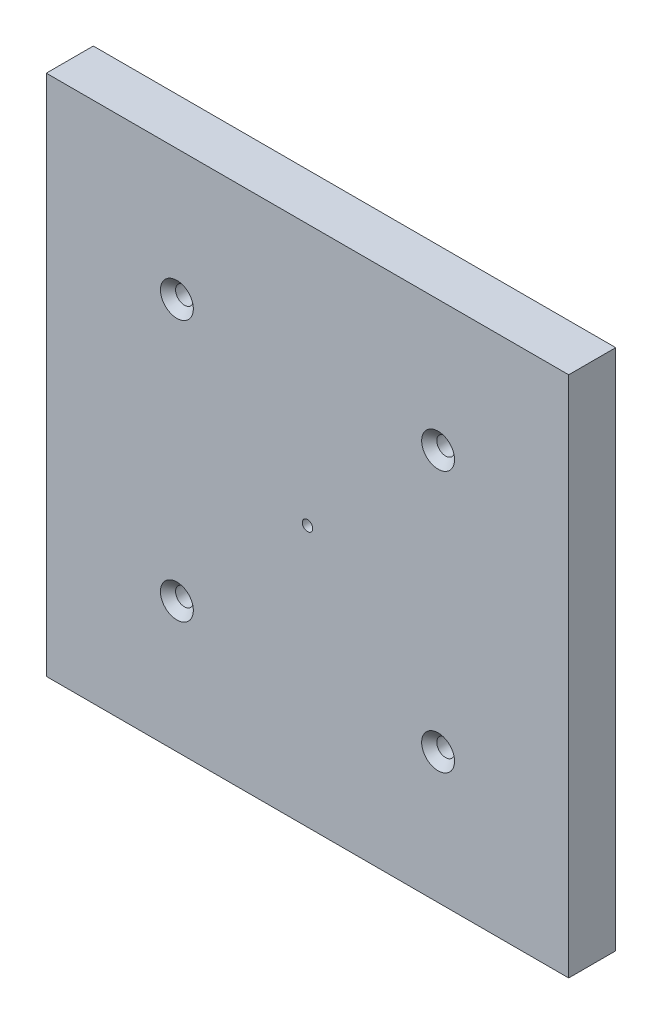
SolidWorks part; units mm, degrees
material "Birch Plywood"
ref_plane "前基準面" through (0, 0, 0) normal (0, 0, 1) x (1, 0, 0)
ref_plane "上基準面" through (0, 0, 0) normal (0, 1, 0) x (1, 0, 0)
ref_plane "右基準面" through (0, 0, 0) normal (1, 0, 0) x (0, 0, -1)
sketch "草圖1" plane through (0, 0, 0) normal (0, 0, 1) x (1, 0, 0)
  line L1 (-50, 50) -> (50, 50)
  line L2 (-50, 50) -> (-50, -50)
  line L3 (-50, -50) -> (50, -50)
  line L4 (50, 50) -> (50, -50)
  line L5 (-50, 50) -> (50, -50) construction
  line L6 (-50, -50) -> (50, 50) construction
  point P0 (0, 0)
  dimension "D1" = 100
  dimension "D2" = 100
extrude "填料-伸長1" add sketch "草圖1" along normal blind 9
sketch "草圖2" plane through (0, 0, 9) normal (0, 0, 1) x (1, 0, 0)
  line L4 (50, -50) -> (50, 50)
  line L5 (50, 50) -> (-50, 50)
  line L6 (-50, 50) -> (-50, -50)
  line L7 (-50, -50) -> (50, -50)
  line L8 (50, -50) -> (50, 50)
  line L9 (50, 50) -> (-50, 50)
  line L10 (-50, 50) -> (-50, -50)
  line L11 (-50, -50) -> (50, -50)
  point P2 (-25, 25)
  point P4 (25, 25)
  point P6 (25, -25)
  point P7 (-25, -25)
  dimension "D2" = 25
  dimension "D3" = 25
  dimension "D4" = 25
  dimension "D5" = 25
  dimension "D6" = 25
  dimension "D1" = 0
hole_wizard "M3 平頭機械螺釘的錐孔1" positions "3D草圖2" profile "草圖4" countersink size "M3" standard "Ansi Metric" end condition through all
sketch3d "3D草圖2"
  point P0 (-25, 25, 9)
  point P3 (25, 25, 9)
  point P6 (25, -25, 9)
  point P9 (-25, -25, 9)
sketch "草圖4" plane through (-25, 25, 9) normal (1, 0, 0) x (0, -1, 0)
  line L0 (0, 0) -> (0, 9)
  line L1 (0, 9) -> (1.725, 9)
  line L2 (1.7, 8.975) -> (1.7, 1.45)
  line L3 (1.7, 1.45) -> (3.15, 0)
  line L5 (3.15, 0) -> (0, 0)
  line L6 (-1.7, 1.45) -> (-3.15, 0) construction
  line L7 (1.725, 9) -> (1.7, 8.975)
  line L8 (-1.725, 9) -> (-1.7, 8.975) construction
  line L11 (0, -6.35) -> (0, 107.95) construction
  dimension "貫穿孔直徑" = 3.4
  dimension "貫穿孔深度" = 9
  dimension "近端錐孔直徑" = 6.3
  dimension "近端錐孔角度" = 90
  dimension "遠端錐孔直徑" = 3.45
  dimension "遠端錐孔角度" = 90
sketch "草圖7" plane through (0, 0, 9) normal (0, 0, 1) x (1, 0, 0)
  point P0 (0, 0)
hole_wizard "Ø2.0mm 定位孔2" positions "3D草圖4" profile "草圖8" hole size "Ø2.0" standard "Ansi Metric"
sketch3d "3D草圖4"
  point P0 (0, 0, 0)
  point P3 (0, 0, 9)
sketch "草圖8" plane through (0, 0, 9) normal (1, 0, 0) x (0, -1, 0)
  line L0 (0, 0) -> (0, 6)
  line L1 (0, 6) -> (1, 5.3991)
  line L2 (1, 5.3991) -> (1, 0)
  line L5 (1, 0) -> (0, 0)
  line L10 (0, 6) -> (-1, 5.3991) construction
  line L11 (0, -6.35) -> (0, 107.95) construction
  dimension "鑽孔直徑" = 2
  dimension "鑽孔深度" = 6
  dimension "導頭角度" = 118
